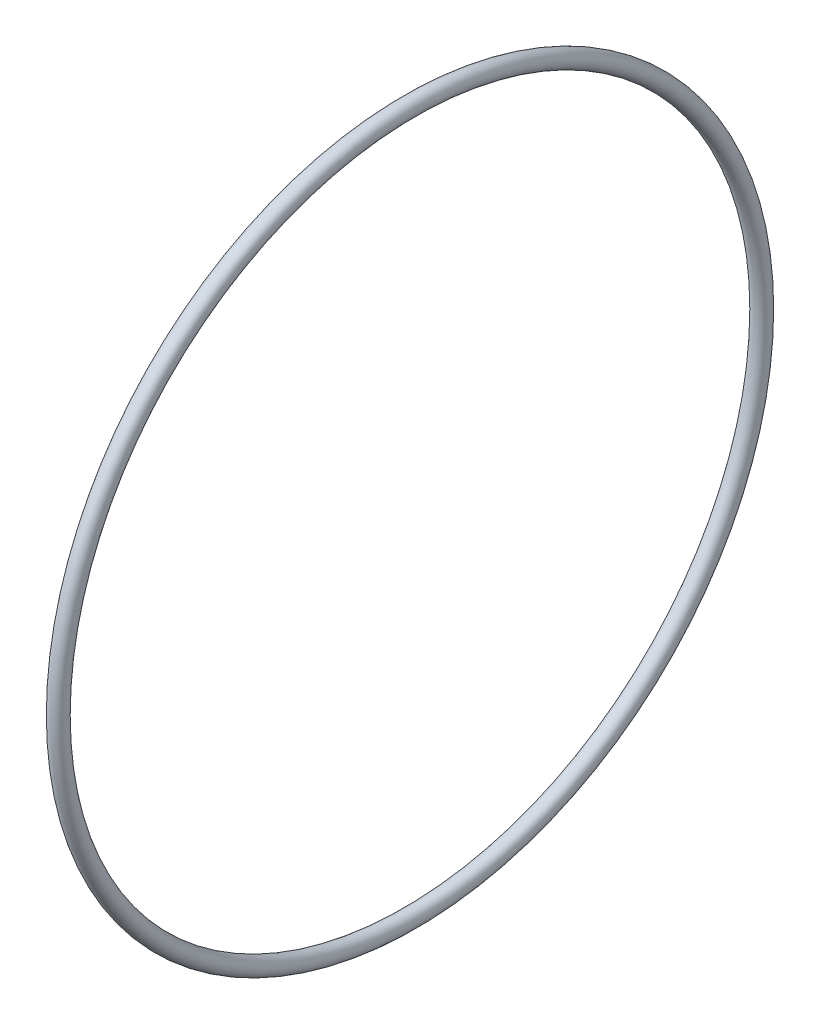
SolidWorks part; units mm, degrees
ref_plane "Front Plane" through (0, 0, 0) normal (0, 0, 1) x (1, 0, 0)
ref_plane "Top Plane" through (0, 0, 0) normal (0, 1, 0) x (1, 0, 0)
ref_plane "Right Plane" through (0, 0, 0) normal (1, 0, 0) x (0, 0, -1)
sketch "Szkic1" plane through (0, 0, 0) normal (1, 0, 0) x (0, 0, -1)
  circle A0 centre (0, 0) radius 62.5
  dimension "D1" = 125
sweep "Wyciągnięcie po ścieżce1" add path "Szkic1" circular profile diameter 3 parameters "D3"=3
